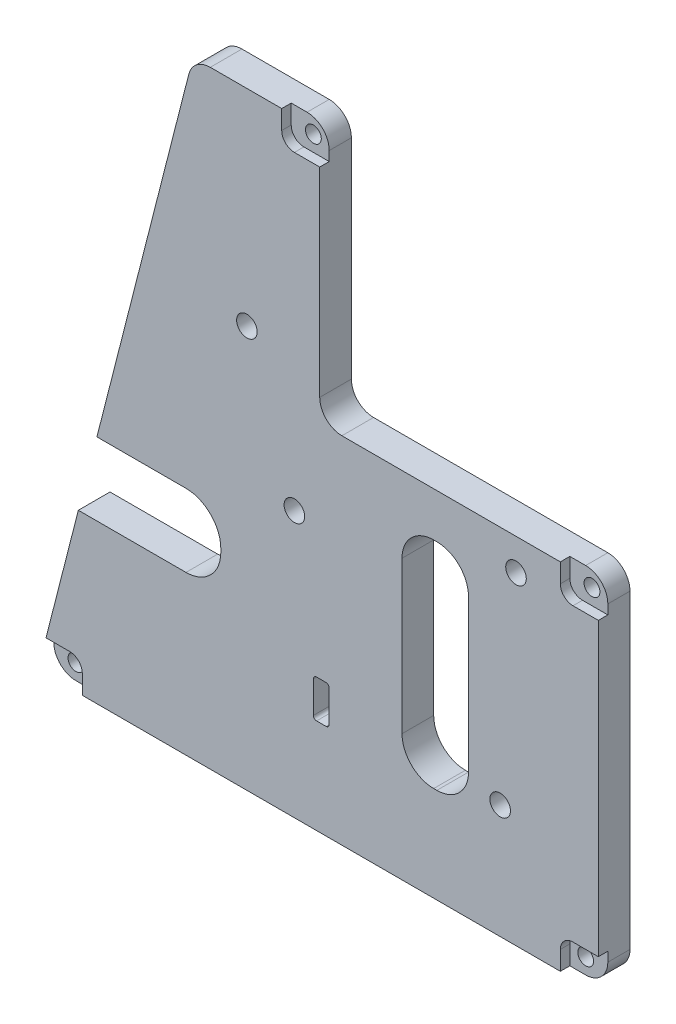
SolidWorks part; units mm, degrees
ref_plane "Front Plane" through (0, 0, 0) normal (0, 0, 1) x (1, 0, 0)
ref_plane "Top Plane" through (0, 0, 0) normal (0, 1, 0) x (1, 0, 0)
ref_plane "Right Plane" through (0, 0, 0) normal (1, 0, 0) x (0, 0, -1)
sketch "Sketch1" plane through (0, 0, 0) normal (0, 0, 1) x (1, 0, 0)
  line L0 (89.2104, -16.9143) -> (15.2104, -16.9143)
  line L1 (-26.3517, 63.0857) -> (1.2104, 63.0857)
  line L3 (-71.7788, -128.9143) -> (89.2104, -128.9143)
  line L4 (96.2104, -23.9143) -> (96.2104, -121.9143)
  line L5 (8.2104, -9.9143) -> (8.2104, 56.0857)
  line L6 (-33.1343, 57.8167) -> (-78.5614, -120.1833)
  arc A0 (-78.5614, -120.1833) -> (-71.7788, -128.9143) centre (-71.7788, -121.9143) ccw
  arc A1 (89.2104, -128.9143) -> (96.2104, -121.9143) centre (89.2104, -121.9143) ccw
  arc A2 (96.2104, -23.9143) -> (89.2104, -16.9143) centre (89.2104, -23.9143) ccw
  arc A3 (15.2104, -16.9143) -> (8.2104, -9.9143) centre (15.2104, -9.9143) cw
  arc A4 (8.2104, 56.0857) -> (1.2104, 63.0857) centre (1.2104, 56.0857) ccw
  arc A5 (-33.1343, 57.8167) -> (-26.3517, 63.0857) centre (-26.3517, 56.0857) cw
  point P10 (96.2104, -128.9143)
  point P13 (96.2104, -16.9143)
  point P16 (8.2104, -16.9143)
  point P19 (8.2104, 63.0857)
  point P22 (-31.7896, 63.0857)
  dimension "D1" = 7
  dimension "D3" = 112
  dimension "D4" = 88
  dimension "D5" = 40
extrude "Boss-Extrude1" add sketch "Sketch1" along normal blind 10
sketch "Sketch2" plane through (0, 0, 10) normal (0, 0, 1) x (1, 0, 0)
  line L0 (-71.7788, -128.9143) -> (89.2104, -128.9143) construction
  line L1 (-68.0292, -55.9143) -> (-34.0292, -55.9143)
  line L2 (-68.0292, -55.9143) -> (-68.0292, -78.9143)
  line L3 (-68.0292, -78.9143) -> (-34.0292, -78.9143)
  line L4 (-23.0292, -66.9143) -> (-23.0292, -67.9143)
  line L5 (-33.1343, 57.8167) -> (-78.5614, -120.1833) construction
  arc A0 (-34.0292, -78.9143) -> (-23.0292, -67.9143) centre (-34.0292, -67.9143) ccw
  arc A1 (-23.0292, -66.9143) -> (-34.0292, -55.9143) centre (-34.0292, -66.9143) ccw
  point P10 (-23.0292, -78.9143)
  point P13 (-23.0292, -55.9143)
  dimension "D5" = 11
  dimension "D1" = 50
  dimension "D2" = 0
  dimension "D3" = 45
  dimension "D4" = 23
extrude "Cut-Extrude1" cut sketch "Sketch2" against normal blind 10
sketch "Sketch3" plane through (0, 0, 10) normal (0, 0, 1) x (1, 0, 0)
  line L0 (1.2104, 63.0857) -> (-26.3517, 63.0857) construction
  line L1 (8.2104, -9.9143) -> (8.2104, 56.0857) construction
  line L4 (96.2104, -121.9143) -> (96.2104, -23.9143) construction
  line L5 (89.2104, -16.9143) -> (15.2104, -16.9143) construction
  line L6 (-71.7788, -128.9143) -> (89.2104, -128.9143) construction
  line L8 (7.2104, -86.9143) -> (10.2104, -86.9143)
  line L9 (6.2104, -87.9143) -> (6.2104, -97.9143)
  line L10 (7.2104, -98.9143) -> (10.2104, -98.9143)
  line L11 (11.2104, -87.9143) -> (11.2104, -97.9143)
  line L12 (44.2104, -30.9143) -> (45.2104, -30.9143)
  line L13 (34.2104, -40.9143) -> (34.2104, -88.9143)
  line L14 (44.2104, -98.9143) -> (45.2104, -98.9143)
  line L15 (55.2104, -40.9143) -> (55.2104, -88.9143)
  circle A0 centre (-14.7896, -1.9143) radius 3.25
  circle A2 centre (0.2104, -44.9143) radius 3.25
  circle A3 centre (70.2104, -26.9143) radius 3.25
  circle A4 centre (65.2104, -92.9143) radius 3.25
  arc A5 (6.2104, -97.9143) -> (7.2104, -98.9143) centre (7.2104, -97.9143) ccw
  arc A6 (10.2104, -98.9143) -> (11.2104, -97.9143) centre (10.2104, -97.9143) ccw
  arc A7 (11.2104, -87.9143) -> (10.2104, -86.9143) centre (10.2104, -87.9143) ccw
  arc A8 (6.2104, -87.9143) -> (7.2104, -86.9143) centre (7.2104, -87.9143) cw
  arc A9 (34.2104, -88.9143) -> (44.2104, -98.9143) centre (44.2104, -88.9143) ccw
  arc A10 (45.2104, -98.9143) -> (55.2104, -88.9143) centre (45.2104, -88.9143) ccw
  arc A11 (55.2104, -40.9143) -> (45.2104, -30.9143) centre (45.2104, -40.9143) ccw
  arc A12 (44.2104, -30.9143) -> (34.2104, -40.9143) centre (44.2104, -40.9143) ccw
  point P26 (11.2104, -98.9143)
  point P29 (11.2104, -86.9143)
  point P32 (6.2104, -86.9143)
  point P39 (34.2104, -98.9143)
  point P42 (55.2104, -98.9143)
  point P47 (34.2104, -30.9143)
  dimension "D3" = 6.5
  dimension "D6" = 12
  dimension "D7" = 6.5
  dimension "D12" = 6.5
  dimension "D15" = 6.5
  dimension "D17" = 1
  dimension "D22" = 10
  dimension "D1" = 65
  dimension "D2" = 23
  dimension "D4" = 85
  dimension "D5" = 30
  dimension "D8" = 96
  dimension "D9" = 28
  dimension "D10" = 10
  dimension "D11" = 26
  dimension "D13" = 31
  dimension "D14" = 36
  dimension "D16" = 5
  dimension "D18" = 41
  dimension "D19" = 68
  dimension "D20" = 14
  dimension "D21" = 21
extrude "Cut-Extrude2" cut sketch "Sketch3" against normal blind 10
sketch "Sketch4" plane through (0, 0, 10) normal (0, 0, 1) x (1, 0, 0)
  line L0 (96.2104, -121.9143) -> (96.2104, -23.9143) construction
  line L1 (96.2104, -118.9143) -> (88.2104, -118.9143)
  line L2 (96.2104, -118.9143) -> (96.2104, -128.9143)
  line L3 (96.2104, -128.9143) -> (84.2104, -128.9143)
  line L4 (84.2104, -122.9143) -> (84.2104, -128.9143)
  line L5 (-71.7788, -128.9143) -> (89.2104, -128.9143) construction
  line L6 (89.2104, -16.9143) -> (15.2104, -16.9143) construction
  line L7 (-66.7788, -128.9143) -> (-78.7788, -128.9143)
  line L8 (-66.7788, -128.9143) -> (-66.7788, -122.9143)
  line L9 (-70.7788, -118.9143) -> (-78.7788, -118.9143)
  line L10 (-78.7788, -128.9143) -> (-78.7788, -118.9143)
  line L11 (84.2104, -16.9143) -> (96.2104, -16.9143)
  line L12 (84.2104, -16.9143) -> (84.2104, -22.9143)
  line L13 (88.2104, -26.9143) -> (96.2104, -26.9143)
  line L14 (96.2104, -16.9143) -> (96.2104, -26.9143)
  line L15 (1.2104, 63.0857) -> (-26.3517, 63.0857) construction
  line L16 (-3.7896, 63.0857) -> (8.2104, 63.0857)
  line L17 (-3.7896, 63.0857) -> (-3.7896, 57.0857)
  line L18 (0.2104, 53.0857) -> (8.2104, 53.0857)
  line L19 (8.2104, 63.0857) -> (8.2104, 53.0857)
  line L20 (8.2104, -9.9143) -> (8.2104, 56.0857) construction
  arc A0 (-78.5614, -120.1833) -> (-71.7788, -128.9143) centre (-71.7788, -121.9143) ccw construction
  arc A1 (88.2104, -118.9143) -> (84.2104, -122.9143) centre (88.2104, -122.9143) ccw
  arc A2 (-66.7788, -122.9143) -> (-70.7788, -118.9143) centre (-70.7788, -122.9143) ccw
  arc A3 (88.2104, -26.9143) -> (84.2104, -22.9143) centre (88.2104, -22.9143) cw
  arc A4 (0.2104, 53.0857) -> (-3.7896, 57.0857) centre (0.2104, 57.0857) cw
  point P17 (84.2104, -118.9143)
  point P20 (-66.7788, -118.9143)
  point P37 (84.2104, -26.9143)
  point P40 (-3.7896, 53.0857)
  dimension "D6" = 4
  dimension "D11" = 4
  dimension "D1" = 10
  dimension "D2" = 12
  dimension "D3" = 12
  dimension "D4" = 7
  dimension "D5" = 10
  dimension "D7" = 10
  dimension "D8" = 12
  dimension "D9" = 10
  dimension "D10" = 12
extrude "Cut-Extrude3" cut sketch "Sketch4" against normal blind 3
sketch "Sketch5" plane through (0, 0, 7) normal (0, 0, 1) x (1, 0, 0)
  line L0 (-70.7788, -118.9143) -> (-78.2375, -118.9143) construction
  line L1 (-66.7788, -128.9143) -> (-66.7788, -122.9143) construction
  line L2 (84.2104, -122.9143) -> (84.2104, -128.9143) construction
  line L3 (96.2104, -118.9143) -> (88.2104, -118.9143) construction
  line L4 (84.2104, -16.9143) -> (15.2104, -16.9143) construction
  line L5 (96.2104, -118.9143) -> (96.2104, -26.9143) construction
  line L6 (-3.7896, 63.0857) -> (-26.3517, 63.0857) construction
  line L7 (8.2104, -9.9143) -> (8.2104, 53.0857) construction
  circle A0 centre (-71.7788, -123.9143) radius 2.5
  circle A1 centre (89.2104, -123.9143) radius 2.5
  circle A2 centre (91.2104, -21.9143) radius 2.5
  circle A3 centre (3.2104, 58.0857) radius 2.5
  dimension "D1" = 5
  dimension "D6" = 5
  dimension "D7" = 5
  dimension "D12" = 5
  dimension "D2" = 5
  dimension "D3" = 5
  dimension "D4" = 5
  dimension "D5" = 5
  dimension "D8" = 5
  dimension "D9" = 5
  dimension "D10" = 5
  dimension "D11" = 5
extrude "Cut-Extrude4" cut sketch "Sketch5" against normal blind 7
